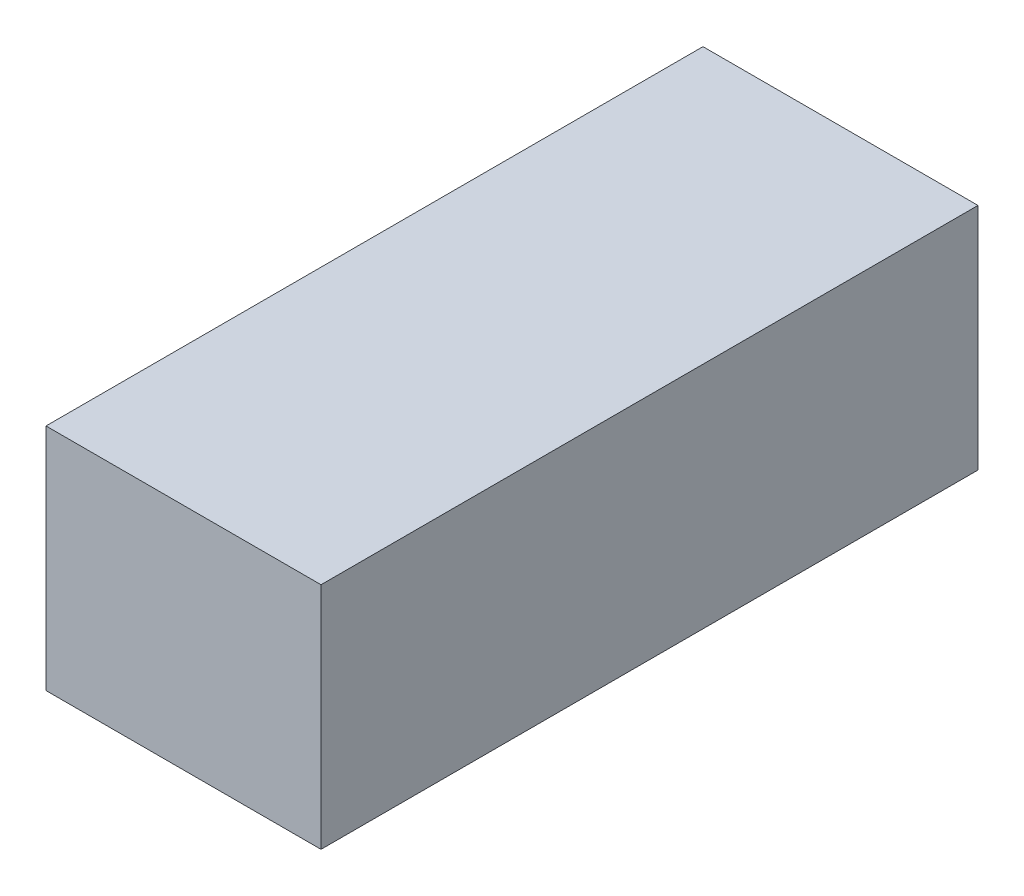
SolidWorks part; units mm, degrees
ref_plane "Front Plane" through (0, 0, 0) normal (0, 0, 1) x (1, 0, 0)
ref_plane "Top Plane" through (0, 0, 0) normal (0, 1, 0) x (1, 0, 0)
ref_plane "Right Plane" through (0, 0, 0) normal (1, 0, 0) x (0, 0, -1)
sketch "Sketch1" plane through (0, 0, 0) normal (0, 0, 1) x (1, 0, 0)
  line L0 (-9, 0) -> (9, 0)
  line L1 (9, 0) -> (9, 15)
  line L2 (9, 15) -> (-9, 15)
  line L3 (-9, 15) -> (-9, 0)
  dimension "D1" = 18
  dimension "D2" = 15
extrude "Boss-Extrude1" add sketch "Sketch1" along normal mid plane 43
